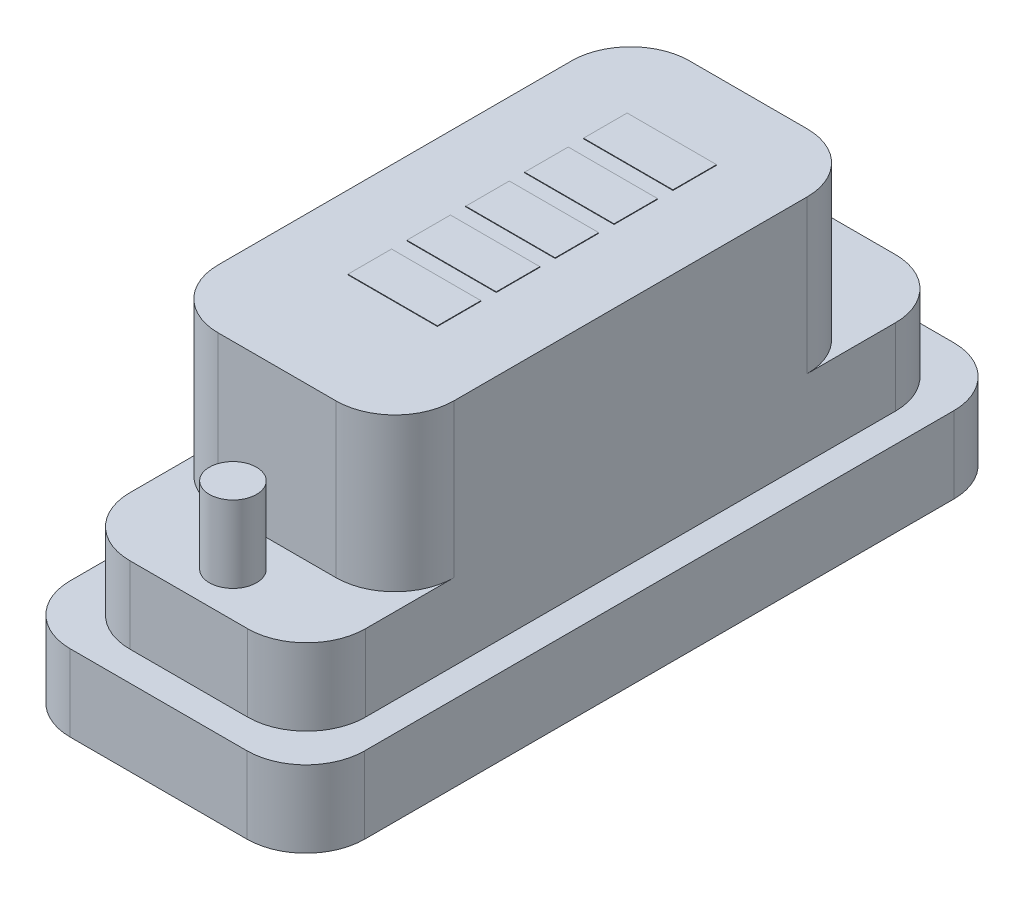
SolidWorks part; units mm, degrees
ref_plane "Front Plane" through (0, 0, 0) normal (0, 0, 1) x (1, 0, 0)
ref_plane "Top Plane" through (0, 0, 0) normal (0, 1, 0) x (1, 0, 0)
ref_plane "Right Plane" through (0, 0, 0) normal (1, 0, 0) x (0, 0, -1)
sketch "Sketch1" plane through (0, 0, 0) normal (0, 1, 0) x (1, 0, 0)
  line L1 (0, 0) -> (50, 0)
  line L2 (0, 0) -> (0, 120)
  line L3 (0, 120) -> (50, 120)
  line L4 (50, 0) -> (50, 120)
  dimension "D1" = 120
  dimension "D2" = 50
extrude "Boss-Extrude1" add sketch "Sketch1" along normal blind 13
fillet "Fillet1" radius 10 4 edges at (0, 6.5, 0) (50, 6.5, 0) (50, 6.5, -120) (0, 6.5, -120)
sketch "Sketch6" plane through (0, 13, 0) normal (0, 1, 0) x (1, 0, 0)
  line L1 (5.115, 115.0063) -> (45.115, 115.0063)
  line L2 (5.115, 115.0063) -> (5.115, 5.0063)
  line L3 (5.115, 5.0063) -> (45.115, 5.0063)
  line L4 (45.115, 115.0063) -> (45.115, 5.0063)
  dimension "D1" = 110
  dimension "D2" = 40
  dimension "D3" = 40
extrude "Boss-Extrude4" add sketch "Sketch6" along normal blind 13
sketch "Sketch7" plane through (0, 26, 0) normal (0, 1, 0) x (1, 0, 0)
  line L0 (45.115, 5.0063) -> (45.115, 115.0063) construction
  line L1 (5.115, 115.0063) -> (5.115, 5.0063) construction
  line L3 (5.115, 100.0063) -> (45.115, 100.0063)
  line L4 (5.115, 100.0063) -> (5.115, 20.0063)
  line L5 (5.115, 20.0063) -> (45.115, 20.0063)
  line L6 (45.115, 100.0063) -> (45.115, 20.0063)
  line L7 (45.115, 115.0063) -> (5.115, 115.0063) construction
  line L8 (5.115, 5.0063) -> (45.115, 5.0063) construction
  dimension "D6" = 15
  dimension "D7" = 15
extrude "Boss-Extrude5" add sketch "Sketch7" along normal blind 26
sketch "Sketch8" plane through (0, 26, 0) normal (0, 1, 0) x (1, 0, 0)
  line L0 (5.115, 115.0063) -> (5.115, 5.0063) construction
  line L1 (45.115, 115.0063) -> (5.115, 115.0063) construction
  line L3 (5.115, 5.0063) -> (45.115, 5.0063) construction
  circle A0 centre (25.115, 107.5063) radius 4
  circle A1 centre (25.115, 12.5063) radius 4
  dimension "D1" = 8
  dimension "D2" = 20
  dimension "D3" = 7.5
  dimension "D4" = 8
  dimension "D5" = 20
  dimension "D6" = 7.5
extrude "Boss-Extrude6" add sketch "Sketch8" along normal blind 13
fillet "Fillet4" radius 10 8 edges at (45.115, 19.5, -5.0063) (5.115, 19.5, -5.0063) (45.115, 39, -20.0063) (5.115, 39, -20.0063) (45.115, 39, -100.0063) (5.115, 39, -100.0063) (45.115, 19.5, -115.0063) (5.115, 19.5, -115.0063)
sketch "Sketch9" plane through (0, 52, 0) normal (0, 1, 0) x (1, 0, 0)
  line L0 (17.5992, 76.9465) -> (17.5992, 69.5457)
  line L1 (17.5992, 86.9465) -> (32.7803, 86.9465)
  line L2 (17.5992, 86.9465) -> (17.5992, 79.5457)
  line L3 (17.5992, 79.5457) -> (32.7803, 79.5457)
  line L4 (32.7803, 86.9465) -> (32.7803, 79.5457)
  line L5 (17.5992, 76.9465) -> (32.7803, 76.9465)
  line L6 (32.7803, 76.9465) -> (32.7803, 69.5457)
  line L7 (17.5992, 69.5457) -> (32.7803, 69.5457)
  line L8 (17.5992, 66.9465) -> (17.5992, 59.5457)
  line L9 (17.5992, 66.9465) -> (32.7803, 66.9465)
  line L10 (32.7803, 66.9465) -> (32.7803, 59.5457)
  line L11 (17.5992, 59.5457) -> (32.7803, 59.5457)
  line L12 (17.5992, 56.9465) -> (17.5992, 49.5457)
  line L13 (17.5992, 56.9465) -> (32.7803, 56.9465)
  line L14 (32.7803, 56.9465) -> (32.7803, 49.5457)
  line L15 (17.5992, 49.5457) -> (32.7803, 49.5457)
  line L16 (17.5992, 46.9465) -> (17.5992, 39.5457)
  line L17 (17.5992, 46.9465) -> (32.7803, 46.9465)
  line L18 (32.7803, 46.9465) -> (32.7803, 39.5457)
  line L19 (17.5992, 39.5457) -> (32.7803, 39.5457)
  dimension "D1" = 5
extrude "Boss-Extrude7" add sketch "Sketch9" along normal blind 0.1
